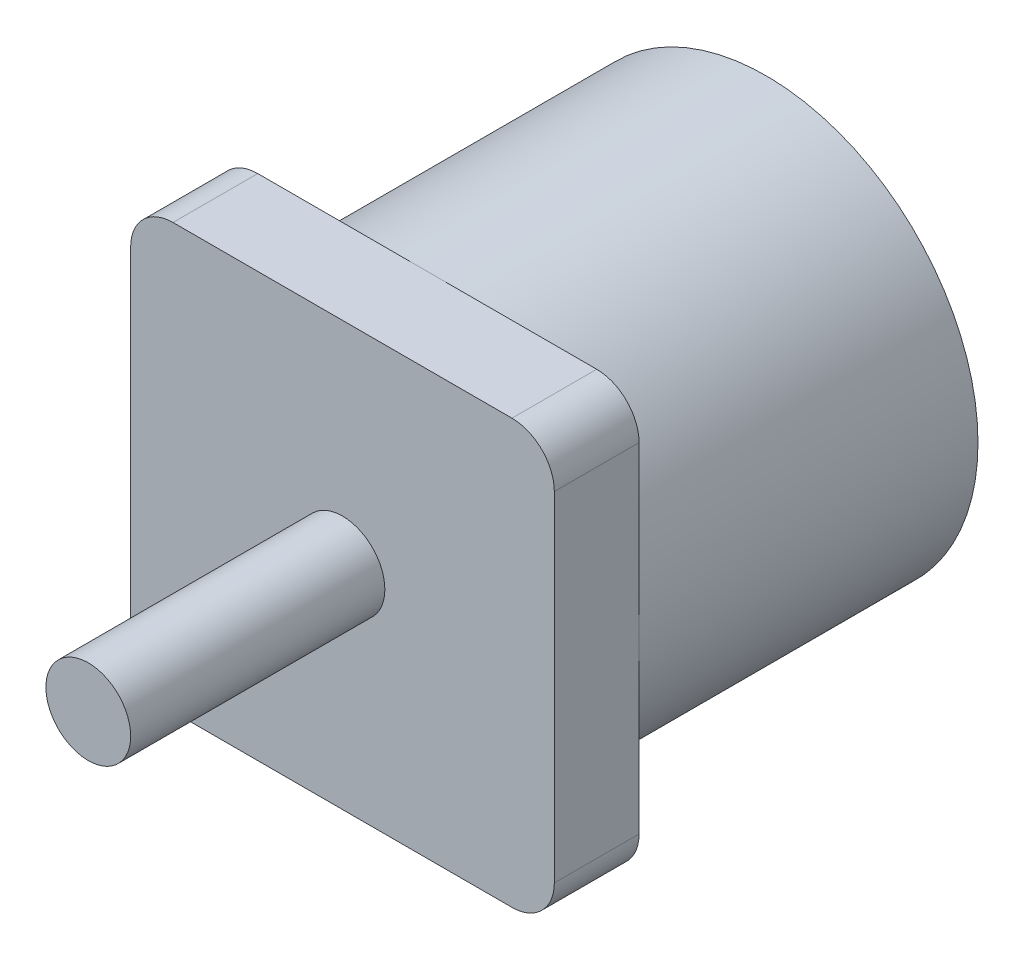
SolidWorks part; units mm, degrees
ref_plane "Front Plane" through (0, 0, 0) normal (0, 0, 1) x (1, 0, 0)
ref_plane "Top Plane" through (0, 0, 0) normal (0, 1, 0) x (1, 0, 0)
ref_plane "Right Plane" through (0, 0, 0) normal (1, 0, 0) x (0, 0, -1)
sketch "Sketch1" plane through (0, 0, 0) normal (0, 0, 1) x (1, 0, 0)
  circle A0 centre (0, 0) radius 25
  dimension "D1" = 50
extrude "Boss-Extrude1" add sketch "Sketch1" along normal blind 50
sketch "Sketch2" plane through (0, 0, 50) normal (0, 0, 1) x (1, 0, 0)
  circle A0 centre (0, 0) radius 5
  dimension "D1" = 10
extrude "Boss-Extrude2" add sketch "Sketch2" along normal blind 30
sketch "Sketch3" plane through (0, 0, 50) normal (0, 0, 1) x (1, 0, 0)
  line L1 (-25, 25) -> (25, 25)
  line L2 (-25, 25) -> (-25, -25)
  line L3 (-25, -25) -> (25, -25)
  line L4 (25, 25) -> (25, -25)
  line L5 (-25, 25) -> (25, -25) construction
  line L6 (-25, -25) -> (25, 25) construction
  point P0 (0, 0)
  dimension "D1" = 50
  dimension "D2" = 50
  dimension "D3" = 50
extrude "Boss-Extrude3" add sketch "Sketch3" against normal blind 10
fillet "Fillet1" radius 5 4 edges at (-25, 25, 45) (-25, -25, 45) (25, -25, 45) (25, 25, 45)
